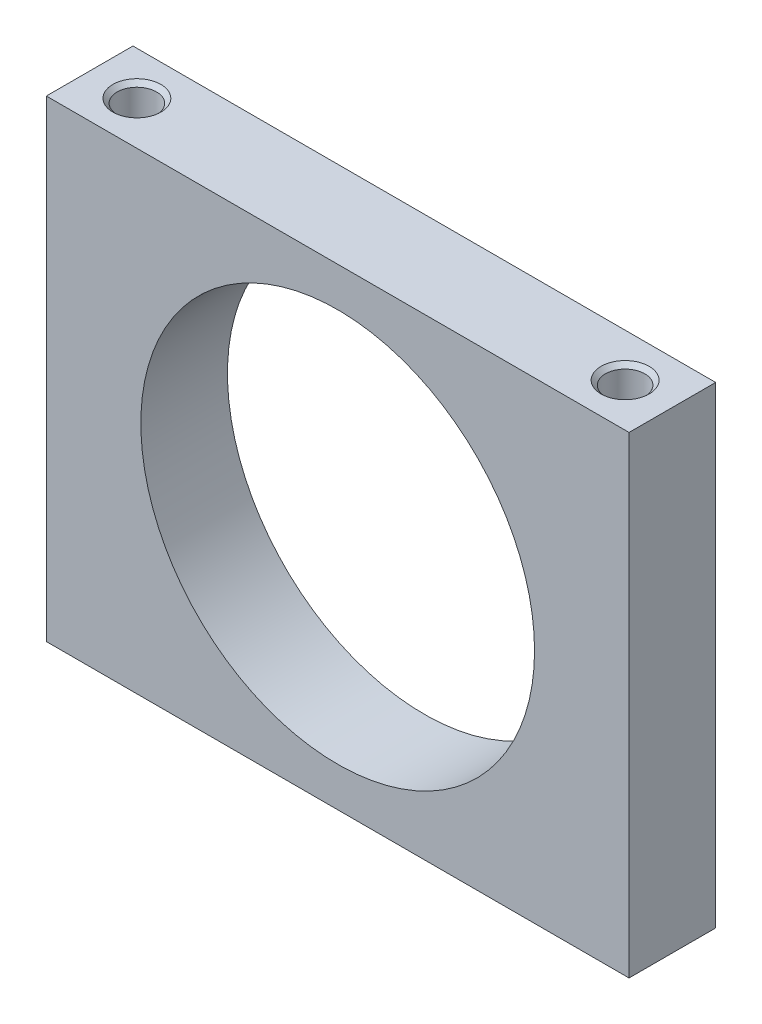
SolidWorks part; units mm, degrees
material "6061 合金"
ref_plane "前视基准面" through (0, 0, 0) normal (0, 0, 1) x (1, 0, 0)
ref_plane "上视基准面" through (0, 0, 0) normal (0, 1, 0) x (1, 0, 0)
ref_plane "右视基准面" through (0, 0, 0) normal (1, 0, 0) x (0, 0, -1)
sketch "草图1" plane through (0, 0, 0) normal (0, 0, 1) x (1, 0, 0)
  line L1 (18.5, 15) -> (-18.5, 15)
  line L2 (18.5, 15) -> (18.5, -15)
  line L3 (18.5, -15) -> (-18.5, -15)
  line L4 (-18.5, 15) -> (-18.5, -15)
  line L5 (18.5, 15) -> (-18.5, -15) construction
  line L6 (18.5, -15) -> (-18.5, 15) construction
  circle A0 centre (0, 0) radius 12.5
  dimension "D3" = 25
  dimension "D1" = 30
  dimension "D2" = 37
extrude "凸台-拉伸1" add sketch "草图1" along normal blind 5.5
hole_wizard "M3 螺纹孔1" positions "草图5" profile "草图6" tap size "M3" standard "GB" end condition through all
sketch "草图5" plane through (0, 15, 0) normal (0, 1, 0) x (1, 0, 0)
  line L1 (0, 0) -> (0, -5.5) construction
  line L2 (18.5, 0) -> (-18.5, 0) construction
  line L3 (18.5, -5.5) -> (-18.5, -5.5) construction
  line L6 (-18.5, -2.75) -> (18.5, -2.75) construction
  line L7 (-18.5, -5.5) -> (-18.5, 0) construction
  line L8 (18.5, -5.5) -> (18.5, 0) construction
  point P0 (-15.5, -2.75)
  point P20 (15.5, -2.75)
  dimension "D1" = 31
sketch "草图6" plane through (-15.5, 15, 2.75) normal (1, 0, 0) x (0, 0, 1)
  line L0 (0, 0) -> (0, 30)
  line L1 (0, 30) -> (1.25, 30)
  line L2 (1.25, 30) -> (1.25, 0.275)
  line L3 (1.25, 0.275) -> (1.525, 0)
  line L5 (1.525, 0) -> (0, 0)
  line L6 (-1.25, 0.275) -> (-1.525, 0) construction
  line L11 (0, -6.35) -> (0, 107.95) construction
  dimension "通孔螺纹孔钻头直径" = 2.5
  dimension "通孔螺纹孔钻头深度" = 30
  dimension "近端锥形沉头孔直径" = 3.05
  dimension "近端锥形沉头孔角度" = 90
cosmetic thread "孔螺蚊线1"
cosmetic thread "孔螺蚊线2"
